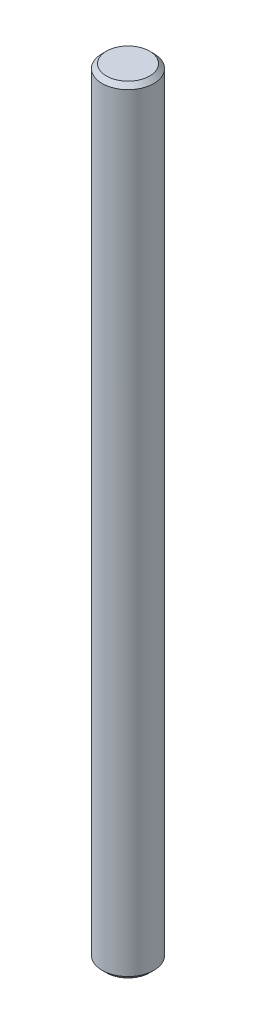
SolidWorks part; units mm, degrees
ref_plane "Front Plane" through (0, 0, 0) normal (0, 0, 1) x (1, 0, 0)
ref_plane "Top Plane" through (0, 0, 0) normal (0, 1, 0) x (1, 0, 0)
ref_plane "Right Plane" through (0, 0, 0) normal (1, 0, 0) x (0, 0, -1)
sketch "Sketch1" plane through (0, 0, 0) normal (0, 1, 0) x (1, 0, 0)
  circle A0 centre (0, 0) radius 3
extrude "Boss-Extrude1" add sketch "Sketch1" along normal blind 90
chamfer "Chamfer1" distance 0.5 angle 45 2 edges at (0, 0, 3) (0, 90, 3)
